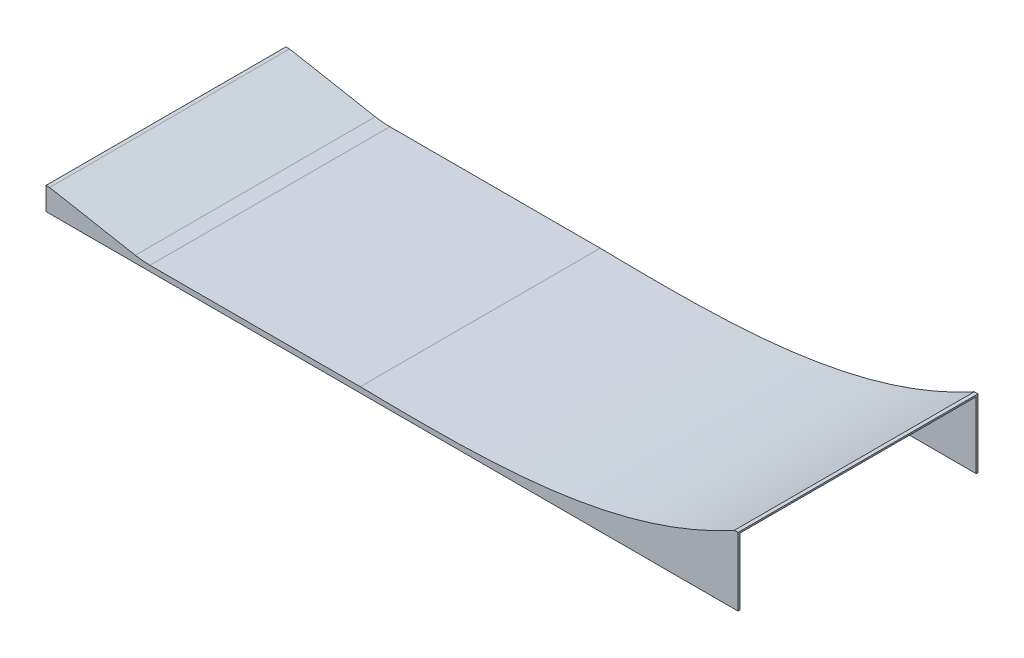
SolidWorks part; units mm, degrees
ref_plane "Front Plane" through (0, 0, 0) normal (0, 0, 1) x (1, 0, 0)
ref_plane "Top Plane" through (0, 0, 0) normal (0, 1, 0) x (1, 0, 0)
ref_plane "Right Plane" through (0, 0, 0) normal (1, 0, 0) x (0, 0, -1)
sketch "Sketch1" plane through (0, 0, 0) normal (0, 0, 1) x (1, 0, 0)
  line L0 (20.2152, 0) -> (595.62, 0)
  line L1 (595.62, 0) -> (1019.98, 11.1123) construction
  line L2 (1019.98, 11.1123) -> (1620.8724, 172.1209) construction
  line L3 (-19.8767, 3.6839) -> (-254.4172, 47.1534)
  line L4 (20.6746, 5) -> (595.6629, 5)
  line L5 (-19.4172, 8.6839) -> (-253.506, 52.0697)
  line L7 (1618.4652, 176.5033) -> (1620.8724, 172.1209)
  line L8 (0.4594, 5) -> (595.6629, 5) construction
  line L9 (0.4594, 5) -> (-253.506, 52.0697) construction
  line L10 (0, 0) -> (595.62, 0) construction
  line L11 (0, 0) -> (-254.4172, 47.1534) construction
  line L12 (1618.4652, 176.5033) -> (1628.4652, 176.5033)
  line L13 (1628.4652, 176.5033) -> (1628.4652, 172.1209)
  line L14 (1628.4652, 172.1209) -> (1620.8724, 172.1209)
  line L15 (-253.506, 52.0697) -> (-263.506, 52.0697)
  line L16 (-263.506, 52.0697) -> (-263.506, 47.1534)
  line L17 (-263.506, 47.1534) -> (-254.4172, 47.1534)
  arc A0 (20.6746, 5) -> (-19.4172, 8.6839) centre (20.6746, 225) cw
  arc A1 (20.2152, 0) -> (-19.8767, 3.6839) centre (20.2152, 220) cw
  spline S0 degree 3 poles (595.62, 0) (948.0425, -6.0519) (1296.6534, -5.9728) (1620.8724, 172.1209) knots 0 0 0 0 1 1 1 1
  spline S1 degree 1 poles (595.6629, 5) (1618.4652, 176.5033) knots 0 0 1 1 construction
  spline S2 degree 3 poles (1618.4652, 176.5033) (1613.4333, 173.7392) (1603.311, 168.2721) (1583.0685, 157.7059) (1557.6618, 145.1185) (1527.0455, 130.9934) (1486.0449, 113.4178) (1434.4726, 93.7308) (1372.0958, 73.5066) (1309.2562, 56.4321) (1224.8897, 37.5321) (1118.4129, 20.5311) (989.2422, 8.7299) (880.6324, 4.3954) (793.2865, 3.2255) (727.5739, 3.246) (661.7075, 3.9131) (617.6663, 4.6222) (595.6629, 5) knots -0.000041 -0.000041 -0.000041 -0.000041 0.015585 0.031211 0.062462 0.093713 0.124964 0.187467 0.24997 0.312472 0.374975 0.49998 0.624985 0.74999 0.812492 0.874995 0.937497 1 1 1 1
  point P17 (0, 0)
  dimension "D9" = 220
  dimension "D1" = 1039.6
  dimension "D2" = 595.62
  dimension "D3" = 165
  dimension "D4" = 178.5
  dimension "D5" = 258.75
  dimension "D6" = 169.5
  dimension "D7" = 424.36
  dimension "D10" = 10
  dimension "D11" = 4.3824
  dimension "D12" = 10
  dimension "D8" = 5
extrude "Boss-Extrude4" add sketch "Sketch1" along normal blind 655.98 contours L13 L14 S0 L0 A1 L3 L17 L16 L15 L5 A0 L4 S2 L12
sketch "Sketch3" plane through (0, 0, 0) normal (0, 0, 1) x (1, 0, 0)
  line L2 (1628.4652, -10) -> (-263.506, -10)
  line L3 (-263.506, -10) -> (-263.506, 52.0697)
  line L4 (1628.4652, 176.5033) -> (1628.4652, -10)
  line L5 (20.2152, 0) -> (595.62, 0) construction
  line L6 (20.2152, 0) -> (595.62, 0)
  line L7 (-254.4172, 47.1534) -> (-19.8767, 3.6839)
  line L8 (1628.4652, 176.5033) -> (1618.4652, 176.5033)
  line L9 (-19.4172, 8.6839) -> (-253.506, 52.0697)
  line L10 (595.6629, 5) -> (20.6746, 5)
  line L11 (1628.4652, 176.5033) -> (1618.4652, 176.5033)
  line L15 (-19.4172, 8.6839) -> (-253.506, 52.0697)
  line L16 (595.6629, 5) -> (20.6746, 5)
  line L22 (1628.4652, 172.1209) -> (1628.4652, 176.5033)
  line L24 (1620.8724, 172.1209) -> (1628.4652, 172.1209)
  line L26 (-263.506, 47.1534) -> (-254.4172, 47.1534)
  line L28 (-263.506, 52.0697) -> (-263.506, 47.1534)
  line L30 (-253.506, 52.0697) -> (-263.506, 52.0697)
  line L31 (-253.506, 52.0697) -> (-263.506, 52.0697)
  arc A2 (-19.8767, 3.6839) -> (20.2152, 0) centre (20.2152, 220) ccw
  arc A3 (-19.4172, 8.6839) -> (20.6746, 5) centre (20.6746, 225) ccw
  arc A5 (-19.4172, 8.6839) -> (20.6746, 5) centre (20.6746, 225) ccw
  spline S2 degree 3 poles (-398.0663, -112.16) (516.2412, 253.3122) (1543.0838, -505.6659) (2286.4391, 918.437) knots -0.946685 -0.946685 -0.946685 -0.946685 1.733037 1.733037 1.733037 1.733037 only from (595.62, 0) to (1620.8724, 172.1209)
  spline S3 degree 3 poles (-2066.8746, -1365.3588) (2144.0369, 585.9621) (1868.2209, 306.5508) (1583.0685, 157.7059) (1557.6618, 145.1185) (1527.0455, 130.9934) (1486.0449, 113.4178) (1434.4726, 93.7308) (1372.0958, 73.5066) (1309.2562, 56.4321) (1224.8897, 37.5321) (1118.4129, 20.5311) (989.2422, 8.7299) (880.6324, 4.3954) (793.2865, 3.2255) (727.5739, 3.246) (-247.9432, 13.1258) (-1262.9085, 147.4382) (1487.4377, -2869.4568) knots -0.818 -0.818 -0.818 -0.818 0.015585 0.031211 0.062462 0.093713 0.124964 0.187467 0.24997 0.312472 0.374975 0.49998 0.624985 0.74999 0.812492 0.874995 0.937497 3.58958 3.58958 3.58958 3.58958 only from (1618.4652, 176.5033) to (595.6629, 5)
  spline S5 degree 3 poles (1618.4652, 176.5033) (1613.4333, 173.7392) (1603.311, 168.2721) (1583.0685, 157.7059) (1557.6618, 145.1185) (1527.0455, 130.9934) (1486.0449, 113.4178) (1434.4726, 93.7308) (1372.0958, 73.5066) (1309.2562, 56.4321) (1224.8897, 37.5321) (1118.4129, 20.5311) (989.2422, 8.7299) (880.6324, 4.3954) (793.2865, 3.2255) (727.5739, 3.246) (661.7075, 3.9131) (617.6663, 4.6222) (595.6629, 5) knots -0.000041 -0.000041 -0.000041 -0.000041 0.015585 0.031211 0.062462 0.093713 0.124964 0.187467 0.24997 0.312472 0.374975 0.49998 0.624985 0.74999 0.812492 0.874995 0.937497 1 1 1 1
  dimension "D2" = 10
  dimension "D1" = 0
extrude "Boss-Extrude5" add sketch "Sketch3" along normal blind 5
sketch "Sketch4" plane through (0, 0, 655.98) normal (0, 0, 1) x (1, 0, 0)
  line L0 (1628.4652, 176.5033) -> (1628.4652, -10)
  line L1 (1628.4652, -10) -> (-263.506, -10)
  line L2 (-263.506, -10) -> (-263.506, 52.0697)
  line L10 (1628.4652, 176.5033) -> (1618.4652, 176.5033)
  line L11 (595.6629, 5) -> (20.6746, 5)
  line L12 (-19.4172, 8.6839) -> (-253.506, 52.0697)
  line L13 (-253.506, 52.0697) -> (-263.506, 52.0697)
  line L14 (-263.506, 52.0697) -> (-263.506, 47.1534)
  line L15 (-263.506, 47.1534) -> (-254.4172, 47.1534)
  line L16 (-254.4172, 47.1534) -> (-19.8767, 3.6839)
  line L17 (20.2152, 0) -> (595.62, 0)
  line L18 (1620.8724, 172.1209) -> (1628.4652, 172.1209)
  line L19 (1628.4652, 172.1209) -> (1628.4652, 176.5033)
  line L20 (1628.4652, 176.5033) -> (1618.4652, 176.5033)
  line L21 (595.6629, 5) -> (20.6746, 5)
  line L22 (-19.4172, 8.6839) -> (-253.506, 52.0697)
  line L23 (-253.506, 52.0697) -> (-263.506, 52.0697)
  arc A2 (-19.4172, 8.6839) -> (20.6746, 5) centre (20.6746, 225) ccw
  arc A3 (-19.8767, 3.6839) -> (20.2152, 0) centre (20.2152, 220) ccw
  arc A4 (-19.4172, 8.6839) -> (20.6746, 5) centre (20.6746, 225) ccw
  spline S2 degree 3 poles (-2066.8746, -1365.3588) (2144.0369, 585.9621) (1868.2209, 306.5508) (1583.0685, 157.7059) (1557.6618, 145.1185) (1527.0455, 130.9934) (1486.0449, 113.4178) (1434.4726, 93.7308) (1372.0958, 73.5066) (1309.2562, 56.4321) (1224.8897, 37.5321) (1118.4129, 20.5311) (989.2422, 8.7299) (880.6324, 4.3954) (793.2865, 3.2255) (727.5739, 3.246) (-247.9432, 13.1258) (-1262.9085, 147.4382) (1487.4377, -2869.4568) knots -0.818 -0.818 -0.818 -0.818 0.015585 0.031211 0.062462 0.093713 0.124964 0.187467 0.24997 0.312472 0.374975 0.49998 0.624985 0.74999 0.812492 0.874995 0.937497 3.58958 3.58958 3.58958 3.58958 only from (1618.4652, 176.5033) to (595.6629, 5)
  spline S3 degree 3 poles (-398.0663, -112.16) (516.2412, 253.3122) (1543.0838, -505.6659) (2286.4391, 918.437) knots -0.946685 -0.946685 -0.946685 -0.946685 1.733037 1.733037 1.733037 1.733037 only from (595.62, 0) to (1620.8724, 172.1209)
  spline S4 degree 3 poles (1618.4652, 176.5033) (1613.4333, 173.7392) (1603.311, 168.2721) (1583.0685, 157.7059) (1557.6618, 145.1185) (1527.0455, 130.9934) (1486.0449, 113.4178) (1434.4726, 93.7308) (1372.0958, 73.5066) (1309.2562, 56.4321) (1224.8897, 37.5321) (1118.4129, 20.5311) (989.2422, 8.7299) (880.6324, 4.3954) (793.2865, 3.2255) (727.5739, 3.246) (661.7075, 3.9131) (617.6663, 4.6222) (595.6629, 5) knots -0.000041 -0.000041 -0.000041 -0.000041 0.015585 0.031211 0.062462 0.093713 0.124964 0.187467 0.24997 0.312472 0.374975 0.49998 0.624985 0.74999 0.812492 0.874995 0.937497 1 1 1 1
  dimension "D1" = 0
extrude "Boss-Extrude6" add sketch "Sketch4" against normal blind 5
